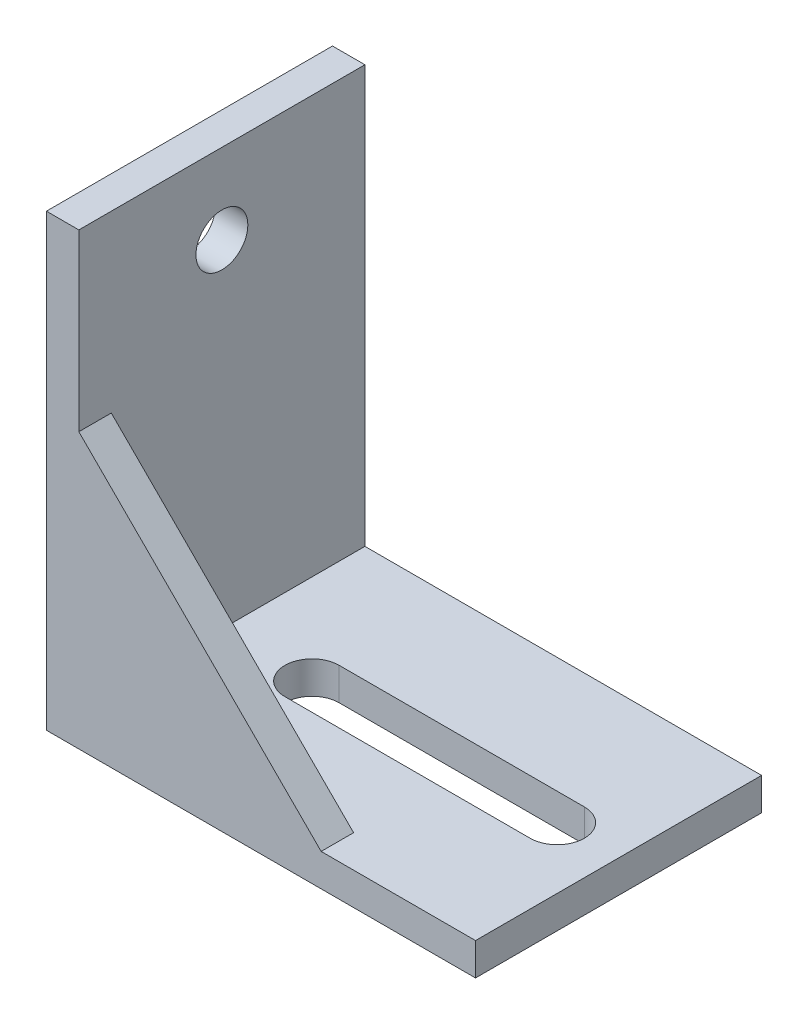
SolidWorks part; units mm, degrees
material "Fundición maleable"
ref_plane "Alzado" through (0, 0, 0) normal (0, 0, 1) x (1, 0, 0)
ref_plane "Planta" through (0, 0, 0) normal (0, 1, 0) x (1, 0, 0)
ref_plane "Vista lateral" through (0, 0, 0) normal (1, 0, 0) x (0, 0, -1)
sketch "Croquis1" plane through (0, 0, 0) normal (1, 0, 0) x (0, 0, -1)
  line L0 (-45.4025, -30) -> (55.245, -30) construction
  line L2 (-35, 80) -> (35, 80) construction
  line L3 (-35, 80) -> (-35, -80) construction
  line L4 (-35, -80) -> (35, -80) construction
  line L5 (35, 80) -> (35, -80) construction
  line L6 (-35, 80) -> (35, -80) construction
  line L7 (-35, -80) -> (35, 80) construction
  line L8 (-35, 80) -> (35, 80)
  line L9 (-35, 80) -> (-35, -30)
  line L10 (-35, -30) -> (35, -30)
  line L11 (35, 80) -> (35, -30)
  circle A0 centre (0, 60.3787) radius 6.35
  dimension "D1" = 12.7
  dimension "D5" = 70
  dimension "D6" = 110
extrude "Saliente-Extruir1" add sketch "Croquis1" along normal blind 7.9375
sketch "Croquis2" plane through (0, -30, 0) normal (0, -1, 0) x (1, 0, 0)
  line L0 (0, 0) -> (105, 0) construction
  line L1 (0, 35) -> (105, 35)
  line L2 (0, 35) -> (0, -35)
  line L3 (0, -35) -> (105, -35)
  line L4 (105, 35) -> (105, -35)
  line L5 (30, 0) -> (90, 0) construction
  line L6 (30, 6.6403) -> (90, 6.6403)
  line L7 (30, -6.6403) -> (90, -6.6403)
  circle A0 centre (30, 0) radius 6.35
  circle A1 centre (90, 0) radius 6.35
  arc A2 (30, 6.6403) -> (30, -6.6403) centre (30, 0) ccw
  arc A3 (90, -6.6403) -> (90, 6.6403) centre (90, 0) ccw
  point P11 (60, 0)
  line M12 (7.9375, -35) -> (7.9375, 35)
  dimension "D1" = 12.7
  dimension "D2" = 12.7
  dimension "D3" = 30
  dimension "D4" = 60
  dimension "D5" = 105
  dimension "D6" = 70
extrude "Saliente-Extruir2" add sketch "Croquis2" against normal blind 7.9375 contours L4 L1 L3 A3 L7 A2 L6 M12
sketch "Croquis3" plane through (0, 0, 35) normal (0, 0, -1) x (-1, 0, 0)
  line L0 (0, 45.1664) -> (-75.1664, -30)
  line L1 (0, 80) -> (0, -30) construction
  line L2 (-105, -30) -> (0, -30) construction
  line L3 (-75.1664, -30) -> (0, -30)
  line L4 (0, -30) -> (0, 45.1664)
  dimension "D1" = 45
extrude "Saliente-Extruir3" add sketch "Croquis3" along normal blind 7.9375
